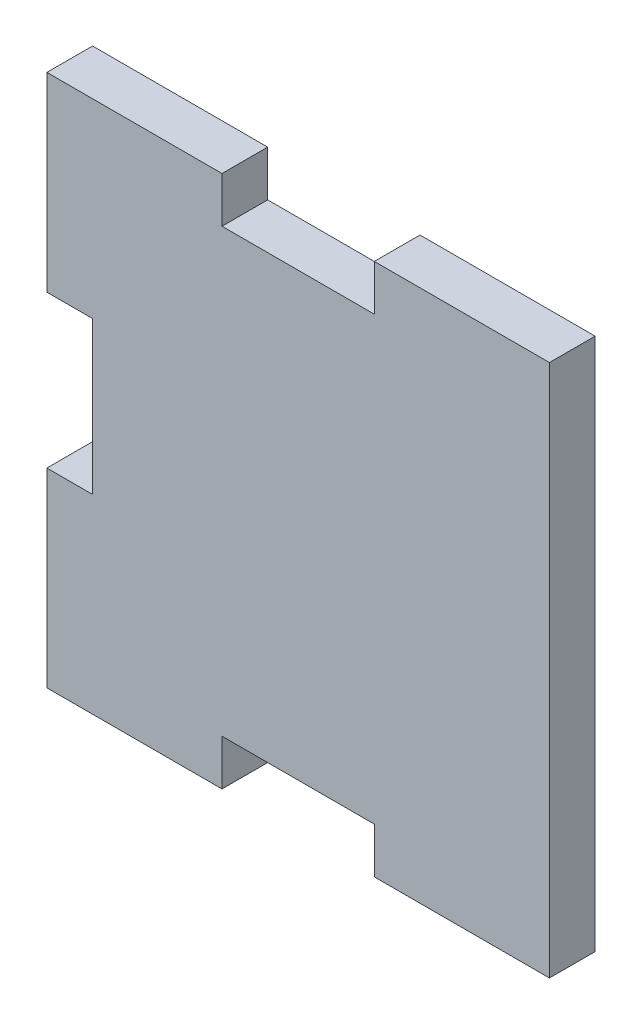
SolidWorks part; units mm, degrees
ref_plane "Plano frontal" through (0, 0, 0) normal (0, 0, 1) x (1, 0, 0)
ref_plane "Plano superior" through (0, 0, 0) normal (0, 1, 0) x (1, 0, 0)
ref_plane "Plano direito" through (0, 0, 0) normal (1, 0, 0) x (0, 0, -1)
sketch "Esboço1" plane through (0, 0, 0) normal (0, 0, 1) x (1, 0, 0)
  line L0 (-16.5, 0) -> (16.5, 0) construction
  line L1 (-16.5, -17.5) -> (16.5, -17.5)
  line L2 (-16.5, -17.5) -> (-16.5, 17.5)
  line L3 (-16.5, 17.5) -> (16.5, 17.5)
  line L4 (16.5, -17.5) -> (16.5, 17.5)
  line L5 (-16.5, -17.5) -> (16.5, 17.5) construction
  line L6 (-16.5, 17.5) -> (16.5, -17.5) construction
  line L7 (5, 14.5) -> (-5, 14.5)
  line L8 (5, 14.5) -> (5, 17.5)
  line L9 (5, 17.5) -> (-5, 17.5)
  line L10 (-5, 14.5) -> (-5, 17.5)
  line L11 (5, 14.5) -> (-5, 17.5) construction
  line L12 (5, 17.5) -> (-5, 14.5) construction
  line L13 (5, -17.5) -> (-5, -17.5)
  line L14 (-5, -14.5) -> (-5, -17.5)
  line L15 (5, -14.5) -> (-5, -14.5)
  line L16 (5, -14.5) -> (5, -17.5)
  line L17 (-16.5, 5) -> (-13.5, 5)
  line L18 (-13.5, 5) -> (-13.5, -5)
  line L19 (-13.5, -5) -> (-16.5, -5)
  line L20 (-16.5, -5) -> (-16.5, 5)
  point P0 (0, 0)
  point P6 (0, 16)
  point P13 (0, 0)
  point P14 (0, 16)
  point P15 (0, 0)
  point P20 (-13.5, 0)
  point P28 (16.5, 0)
  dimension "D5" = 3
  dimension "D1" = 35
  dimension "D2" = 10
  dimension "D3" = 10
  dimension "D4" = 3
  dimension "D8" = 11.5
extrude "Ressalto-extrusão1" add sketch "Esboço1" along normal blind 3 contours L15 L16 L1 L4 L3 L8 L7 L10 L2 L14
